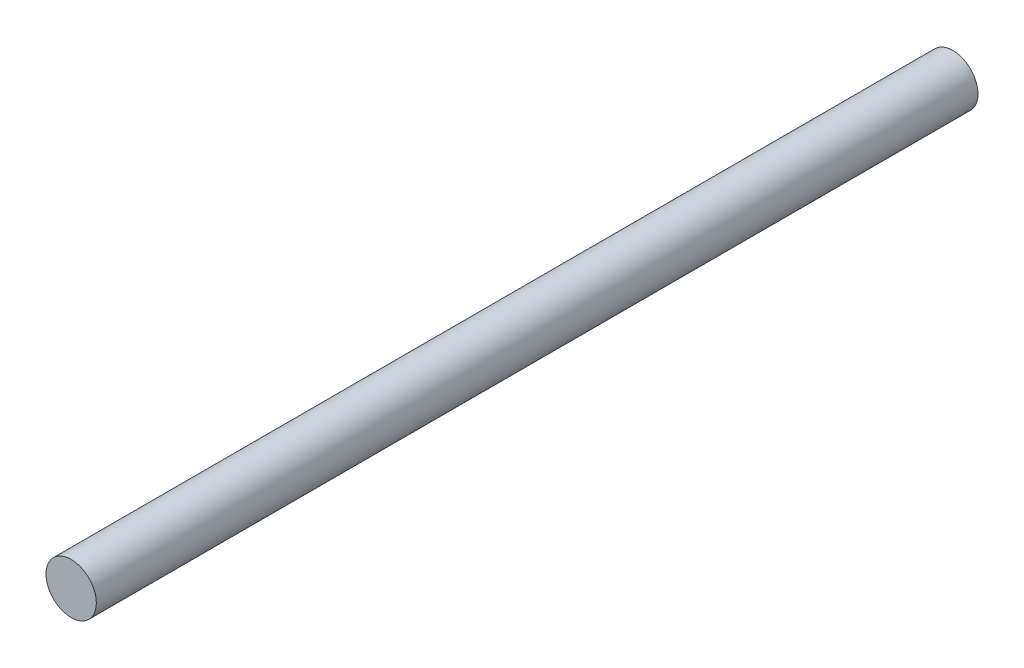
SolidWorks part; units mm, degrees
ref_plane "Спереди" through (0, 0, 0) normal (0, 0, 1) x (1, 0, 0)
ref_plane "Сверху" through (0, 0, 0) normal (0, 1, 0) x (1, 0, 0)
ref_plane "Справа" through (0, 0, 0) normal (1, 0, 0) x (0, 0, -1)
sketch "Эскиз1" plane through (0, 0, 0) normal (0, 0, 1) x (1, 0, 0)
  circle A0 centre (0, 0) radius 2
  dimension "D1" = 4
extrude "Бобышка-Вытянуть1" add sketch "Эскиз1" along normal blind 70
